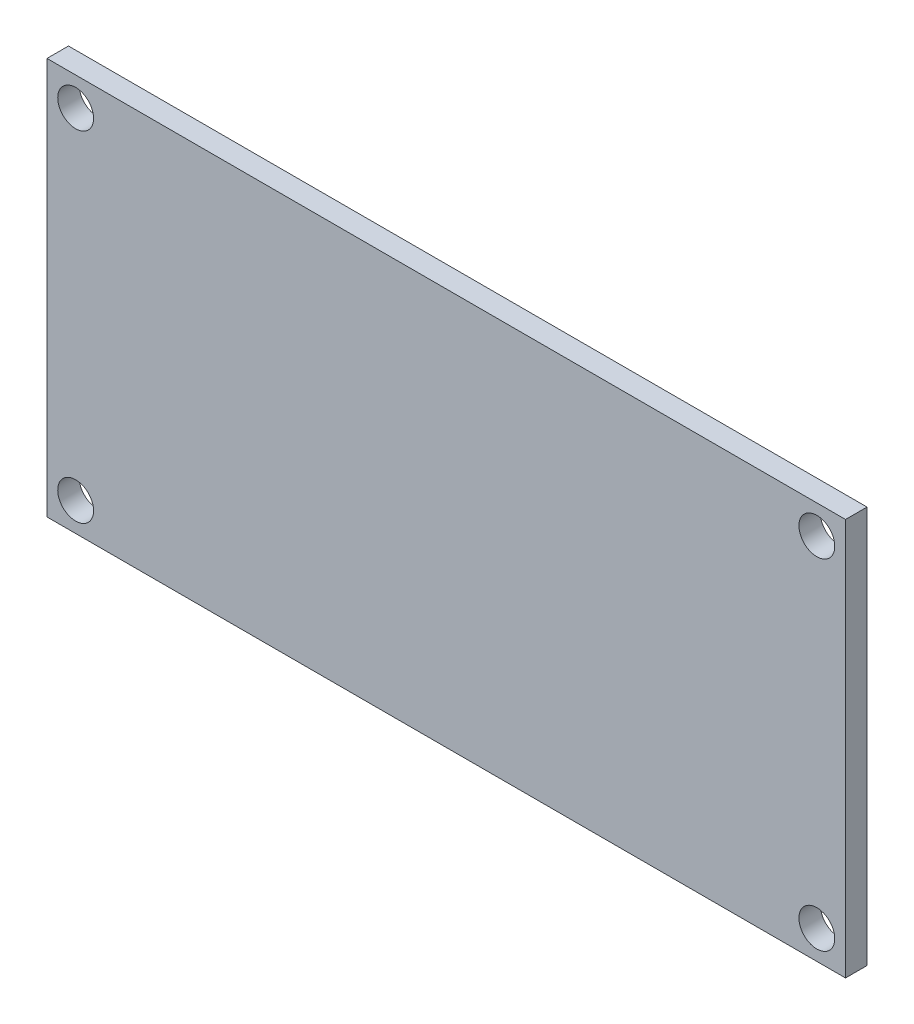
SolidWorks part; units mm, degrees
ref_plane "前视基准面" through (0, 0, 0) normal (0, 0, 1) x (1, 0, 0)
ref_plane "上视基准面" through (0, 0, 0) normal (0, 1, 0) x (1, 0, 0)
ref_plane "右视基准面" through (0, 0, 0) normal (1, 0, 0) x (0, 0, -1)
other "Configuration Table"
sketch "草图1" plane through (0, 0, 0) normal (0, 0, 1) x (1, 0, 0)
  line L1 (-55.7, 27.7) -> (55.7, 27.7)
  line L2 (-55.7, 27.7) -> (-55.7, -27.7)
  line L3 (-55.7, -27.7) -> (55.7, -27.7)
  line L4 (55.7, 27.7) -> (55.7, -27.7)
  point P4 (0, 27.7)
  point P5 (55.7, 0)
  dimension "D1" = 111.4
  dimension "D2" = 55.4
extrude "凸台-拉伸1" add sketch "草图1" along normal blind 3
sketch "草图2" plane through (0, 0, 0) normal (0, 0, -1) x (-1, 0, 0)
  line L0 (-55.7, -27.7) -> (-55.7, 27.7) construction
  line L1 (-55.7, 27.7) -> (55.7, 27.7) construction
  line L2 (55.7, -27.7) -> (-55.7, -27.7) construction
  line L3 (55.7, 27.7) -> (55.7, -27.7) construction
  circle A0 centre (-51.7, 23.7) radius 2.5
  circle A1 centre (-51.7, -23.7) radius 2.5
  circle A2 centre (51.7, -23.7) radius 2.5
  circle A3 centre (51.7, 23.7) radius 2.5
  dimension "D1" = 5
  dimension "D2" = 4
  dimension "D3" = 4
  dimension "D4" = 4
  dimension "D5" = 4
extrude "切除-拉伸1" cut sketch "草图2" against normal through all
